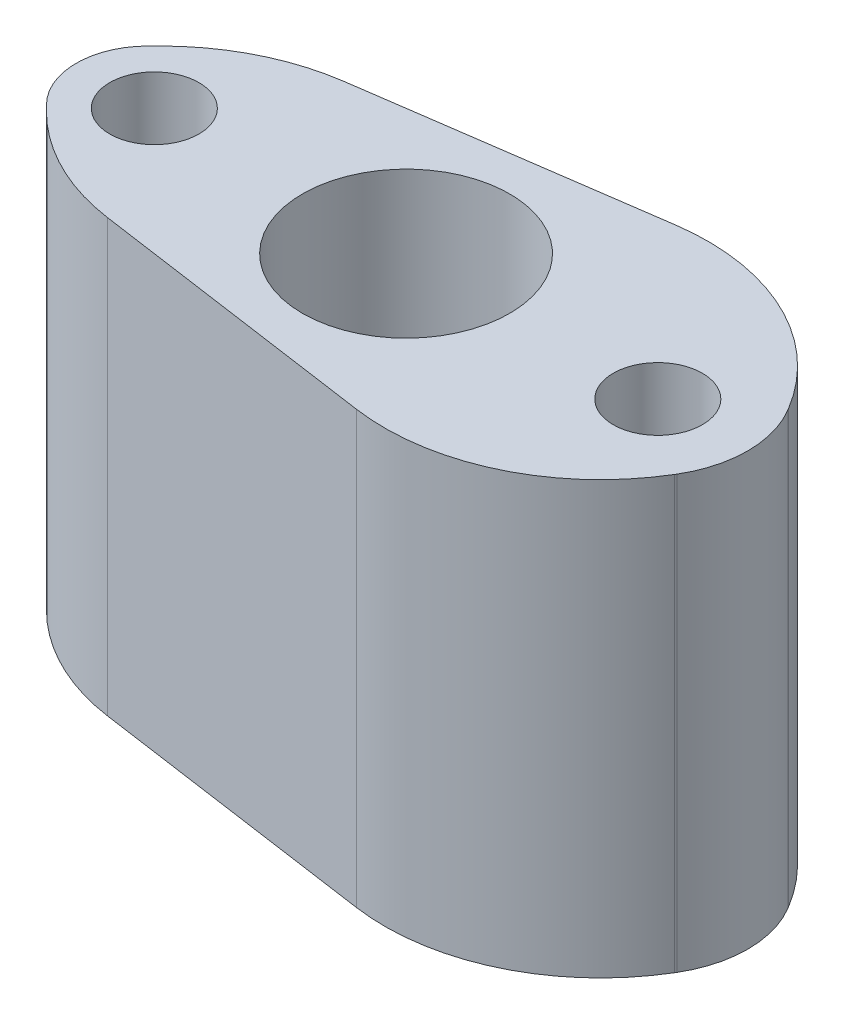
SolidWorks part; units mm, degrees
ref_plane "Front Plane" through (0, 0, 0) normal (0, 0, 1) x (1, 0, 0)
ref_plane "Top Plane" through (0, 0, 0) normal (0, 1, 0) x (1, 0, 0)
ref_plane "Right Plane" through (0, 0, 0) normal (1, 0, 0) x (0, 0, -1)
sketch "Sketch1" plane through (0, 0, 0) normal (0, 1, 0) x (1, 0, 0)
  line L0 (2.2685, 0.3856) -> (2.2624, 0.3958)
  line L1 (0.7639, 1.1091) -> (-1.255, 0.8207)
  line L2 (-2.1036, 0.3964) -> (-2.1464, 0.3536)
  line L3 (-2.1464, -0.3536) -> (-2.1036, -0.3964)
  line L4 (-1.255, -0.8207) -> (0.7642, -1.1092)
  line L5 (2.2624, -0.3961) -> (2.2684, -0.3861)
  circle A0 centre (0, 0) radius 0.72
  circle A1 centre (1.75, 0) radius 0.31
  circle A2 centre (-1.75, 0) radius 0.31
  arc A3 (-2.1464, 0.3536) -> (-2.1464, -0.3536) centre (-1.7929, 0) ccw
  arc A4 (-1.255, 0.8207) -> (-2.1036, 0.3964) centre (-1.0429, -0.6642) ccw
  arc A5 (-1.255, -0.8207) -> (-2.1036, -0.3964) centre (-1.0429, 0.6642) cw
  arc A6 (2.2624, 0.3958) -> (0.7639, 1.1091) centre (0.9761, -0.3758) ccw
  arc A7 (2.2624, -0.3961) -> (0.7642, -1.1092) centre (0.9763, 0.3758) cw
  arc A8 (2.2684, -0.3861) -> (2.2685, 0.3856) centre (1.6254, -0.0002) ccw
  point P7 (-2.5, 0)
  point P10 (-1.75, 0.75)
  point P11 (-1.75, -0.75)
  point P12 (1.75, 1.25)
  point P13 (2.5, -0.0003)
  point P14 (1.75, -1.25)
  point P21 (-2.5, 0)
  point P24 (-1.75, 0.75)
  point P25 (-2.5, 0)
  point P28 (-1.75, -0.75)
  point P31 (1.75, 1.25)
  point P34 (1.75, -1.25)
  point P37 (2.5, -0.0003)
  dimension "D1" = 0.5
  dimension "D2" = 1.5
  dimension "D3" = 1.5
  dimension "D4" = 1.5
  dimension "D5" = 1.5
  dimension "D6" = 0.75
extrude "Boss-Extrude1" add sketch "Sketch1" along normal blind 3
